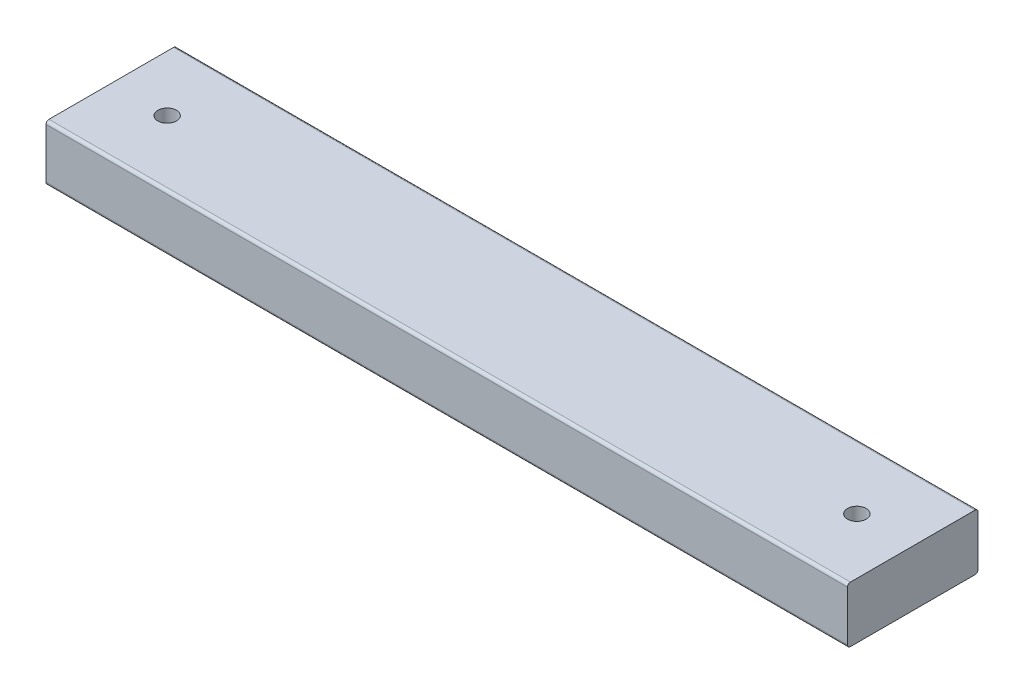
SolidWorks part; units mm, degrees
ref_plane "Front Plane" through (0, 0, 0) normal (0, 0, 1) x (1, 0, 0)
ref_plane "Top Plane" through (0, 0, 0) normal (0, 1, 0) x (1, 0, 0)
ref_plane "Right Plane" through (0, 0, 0) normal (1, 0, 0) x (0, 0, -1)
sketch "Sketch1" plane through (0, 0, 0) normal (1, 0, 0) x (0, 0, -1)
  line L1 (-44.45, -19.05) -> (44.45, -19.05)
  line L2 (-44.45, -19.05) -> (-44.45, 19.05)
  line L3 (-44.45, 19.05) -> (44.45, 19.05)
  line L4 (44.45, -19.05) -> (44.45, 19.05)
  line L5 (-44.45, -19.05) -> (44.45, 19.05) construction
  line L6 (-44.45, 19.05) -> (44.45, -19.05) construction
  point P0 (0, 0)
  dimension "D1" = 38.1
  dimension "D2" = 88.9
extrude "Boss-Extrude1" add sketch "Sketch1" along normal blind 546.1
fillet "Fillet1" radius 2 4 edges at (273.05, 19.05, 44.45) (273.05, 19.05, -44.45) (273.05, -19.05, -44.45) (273.05, -19.05, 44.45)
sketch "Sketch3" plane through (0, 19.05, 0) normal (0, 1, 0) x (1, 0, 0)
  line L0 (546.1, 42.45) -> (546.1, -42.45) construction
  circle A0 centre (508, 0) radius 6.35
  dimension "D1" = 12.7
  dimension "D2" = 38.1
extrude "Cut-Extrude2" cut sketch "Sketch3" against normal through all
ref_plane "Plane1" through (273.05, 0, 0) normal (1, 0, 0) x (0, 0, -1)
mirror "Mirror1" about plane through (273.05, 0, 0) normal (1, 0, 0) of "Cut-Extrude2"
